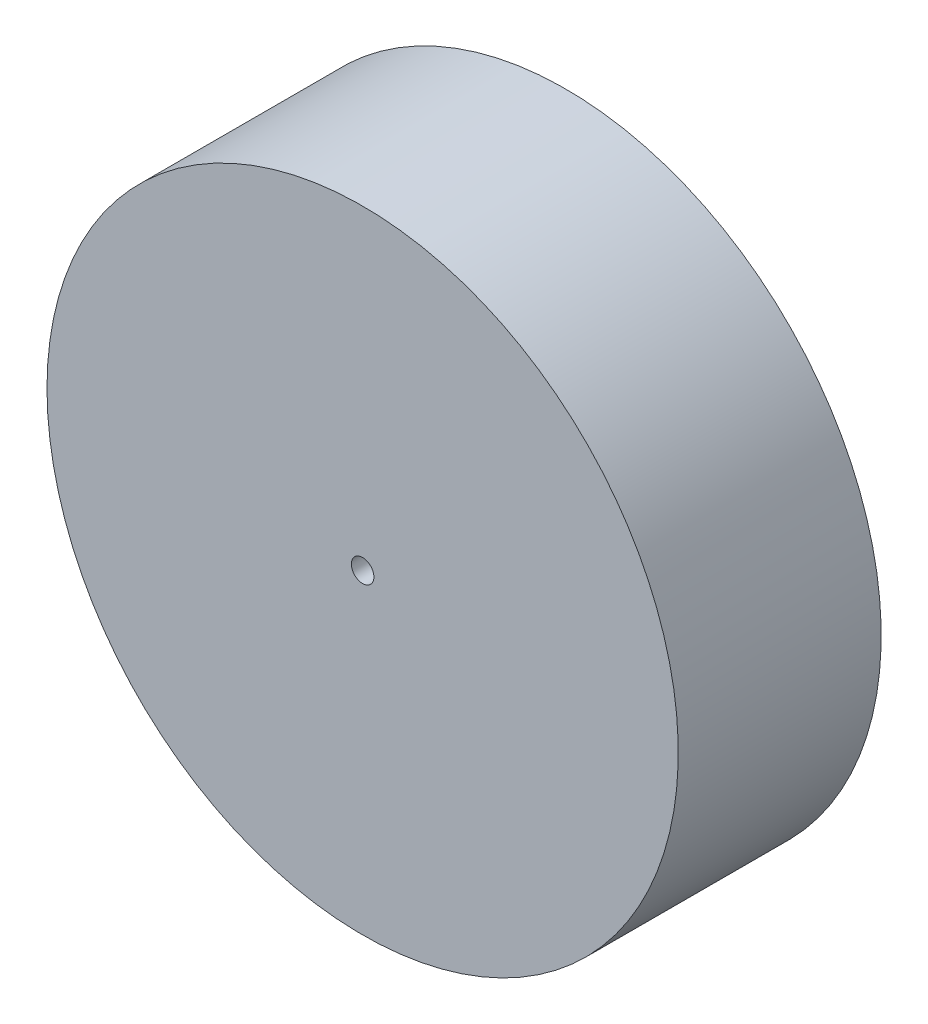
SolidWorks part; units mm, degrees
ref_plane "Front Plane" through (0, 0, 0) normal (0, 0, 1) x (1, 0, 0)
ref_plane "Top Plane" through (0, 0, 0) normal (0, 1, 0) x (1, 0, 0)
ref_plane "Right Plane" through (0, 0, 0) normal (1, 0, 0) x (0, 0, -1)
sketch "Sketch1" plane through (0, 0, 0) normal (0, 0, 1) x (1, 0, 0)
  circle A0 centre (0, 0) radius 70
  dimension "D1" = 140
extrude "Boss-Extrude1" add sketch "Sketch1" along normal blind 45
sketch "Sketch3" plane through (0, 0, 45) normal (0, 0, 1) x (1, 0, 0)
  circle A0 centre (0, 0) radius 2.5
  dimension "D1" = 5
extrude "Cut-Extrude1" cut sketch "Sketch3" against normal blind 20
